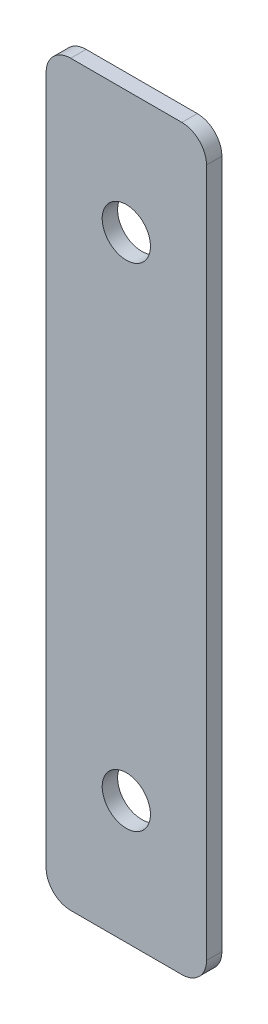
SolidWorks part; units mm, degrees
ref_plane "Front Plane" through (0, 0, 0) normal (0, 0, 1) x (1, 0, 0)
ref_plane "Top Plane" through (0, 0, 0) normal (0, 1, 0) x (1, 0, 0)
ref_plane "Right Plane" through (0, 0, 0) normal (1, 0, 0) x (0, 0, -1)
sketch "Sketch1" plane through (0, 0, 0) normal (0, 0, 1) x (1, 0, 0)
  line L0 (0, -43.815) -> (0, 6.985) construction
  line L1 (-8.2804, 254.635) -> (-8.2804, -254.635) construction
  line L2 (5.7404, -56.515) -> (-5.7404, -56.515)
  line L3 (8.2804, -53.975) -> (8.2804, 17.145)
  line L4 (5.7404, 19.685) -> (-5.7404, 19.685)
  line L5 (-8.2804, -53.975) -> (-8.2804, 17.145)
  line L6 (8.2804, -56.515) -> (-8.2804, 19.685) construction
  line L7 (8.2804, 19.685) -> (-8.2804, -56.515) construction
  circle A0 centre (0, -43.815) radius 2.4892 construction
  circle A1 centre (0, 6.985) radius 2.4892 construction
  circle A2 centre (0, -43.815) radius 2.4892
  circle A3 centre (0, 6.985) radius 2.4892
  arc A4 (-8.2804, -53.975) -> (-5.7404, -56.515) centre (-5.7404, -53.975) ccw
  arc A5 (8.2804, -53.975) -> (5.7404, -56.515) centre (5.7404, -53.975) cw
  arc A6 (5.7404, 19.685) -> (8.2804, 17.145) centre (5.7404, 17.145) cw
  arc A7 (-5.7404, 19.685) -> (-8.2804, 17.145) centre (-5.7404, 17.145) ccw
  point P6 (0, -18.415)
  point P11 (-0.0286, -18.5495)
  point P12 (0, -18.415)
  point P25 (-7.5909, -73.815)
  point P26 (0, 0)
  dimension "D2" = 2.54
  dimension "D1" = 12.7
extrude "Boss-Extrude1" add sketch "Sketch1" along normal blind 1.5875
